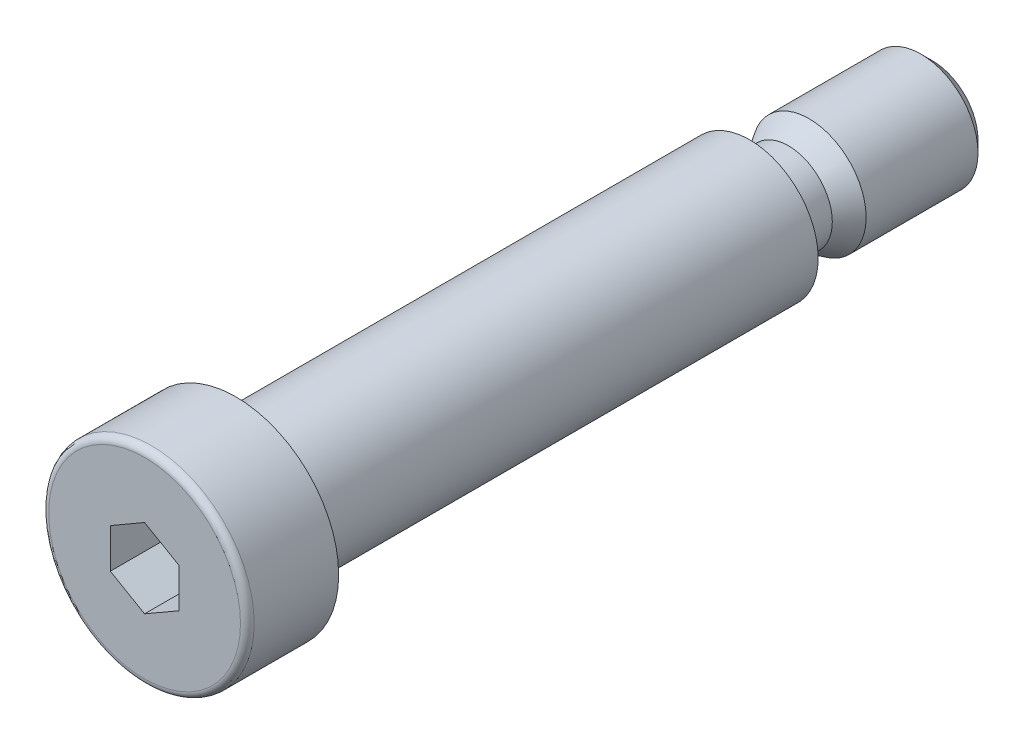
SolidWorks part; units mm, degrees
material "1.0545 (S355N)"
ref_plane "Płaszczyzna przednia" through (0, 0, 0) normal (0, 0, 1) x (1, 0, 0)
ref_plane "Płaszczyzna górna" through (0, 0, 0) normal (0, 1, 0) x (1, 0, 0)
ref_plane "Płaszczyzna prawa" through (0, 0, 0) normal (1, 0, 0) x (0, 0, -1)
sketch "Szkic1" plane through (0, 0, 0) normal (0, 1, 0) x (1, 0, 0)
  line L0 (5, 27.7) -> (3.85, 25.89)
  line L1 (9, -30.5) -> (-9, -30.5)
  line L2 (9, -30.5) -> (9, -22.5)
  line L3 (9, -22.5) -> (-9, -22.5)
  line L4 (-9, -30.5) -> (-9, -22.5)
  line L5 (6, -22.5) -> (-6, -22.5)
  line L6 (6, -22.5) -> (6, 22.5)
  line L7 (6, 22.5) -> (-6, 22.5)
  line L8 (-6, -22.5) -> (-6, 22.5)
  line L9 (-3.85, 22.5) -> (3.85, 22.5)
  line L10 (-3.85, 22.5) -> (-3.85, 25.89)
  line L11 (-3.85, 25.89) -> (3.85, 25.89)
  line L12 (3.85, 22.5) -> (3.85, 25.89)
  line L13 (5, 27.7) -> (5, 37.5)
  line L14 (5, 37.5) -> (4, 38.5)
  line L15 (4, 38.5) -> (-4, 38.5)
  line L16 (-4, 38.5) -> (-5, 37.5)
  line L17 (-5, 37.5) -> (-5, 27.7)
  line L18 (-5, 27.7) -> (-3.85, 25.89)
  line L19 (5, 27.7) -> (-5, 27.7) construction
  line L20 (5, 37.5) -> (-5, 37.5) construction
  line L21 (0, -19.9356) -> (0, 25.6583) construction
  line L22 (0, -30.5) -> (0, 38.5)
  point P4 (0, -22.5)
  point P14 (0, -22.5)
  point P15 (0, 22.5)
  point P16 (0, 22.5)
  point P17 (-6, 0)
  point P23 (0, 27.7)
  point P25 (0, 38.5)
  point P26 (0, 25.89)
  point P27 (0, 37.5)
  dimension "D1" = 18
  dimension "D2" = 8
  dimension "D3" = 12
  dimension "l1" = 45
  dimension "D5" = 7.7
  dimension "D6" = 16
  dimension "D7" = 10
  dimension "D8" = 8
  dimension "D9" = 1
  dimension "D10" = 1.81
  dimension "D11" = 9.8
revolve "Obrót1" add sketch "Szkic1" angle 360 about L22
sketch "Szkic2" plane through (0, 0, 30.5) normal (0, 0, 1) x (1, 0, 0)
  line L1 (3, 1.7321) -> (0, 3.4641)
  line L2 (0, 3.4641) -> (-3, 1.7321)
  line L3 (-3, 1.7321) -> (-3, -1.7321)
  line L4 (-3, -1.7321) -> (0, -3.4641)
  line L5 (0, -3.4641) -> (3, -1.7321)
  line L6 (3, -1.7321) -> (3, 1.7321)
  circle A0 centre (0, 0) radius 3 construction
  dimension "D1" = 6
extrude "Wytnij-wyciągnięcie1" cut sketch "Szkic2" against normal blind 4.9
fillet "Zaokrąglenie1" radius 0.6 1 edges at (9, 0, 30.5)
